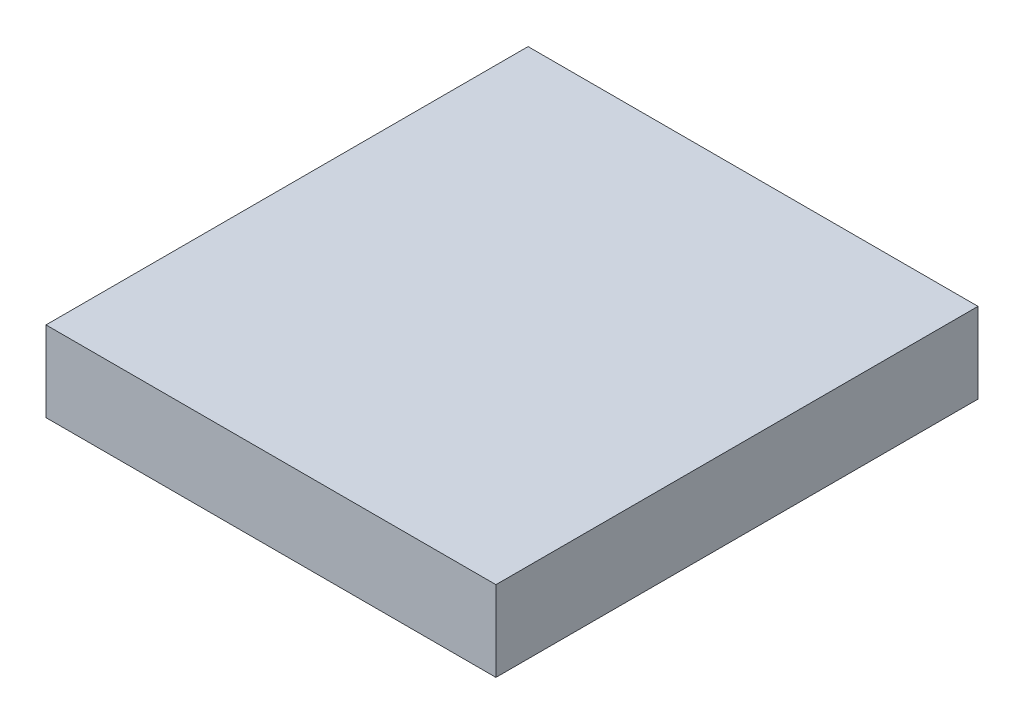
SolidWorks part; units mm, degrees
ref_plane "Front Plane" through (0, 0, 0) normal (0, 0, 1) x (1, 0, 0)
ref_plane "Top Plane" through (0, 0, 0) normal (0, 1, 0) x (1, 0, 0)
ref_plane "Right Plane" through (0, 0, 0) normal (1, 0, 0) x (0, 0, -1)
sketch "Sketch1" plane through (0, 0, 0) normal (0, 1, 0) x (1, 0, 0)
  line L1 (0, 0) -> (28, 0)
  line L2 (0, 0) -> (0, 30)
  line L3 (0, 30) -> (28, 30)
  line L4 (28, 0) -> (28, 30)
  dimension "D1" = 28
  dimension "D2" = 30
extrude "Boss-Extrude1" add sketch "Sketch1" along normal blind 5
